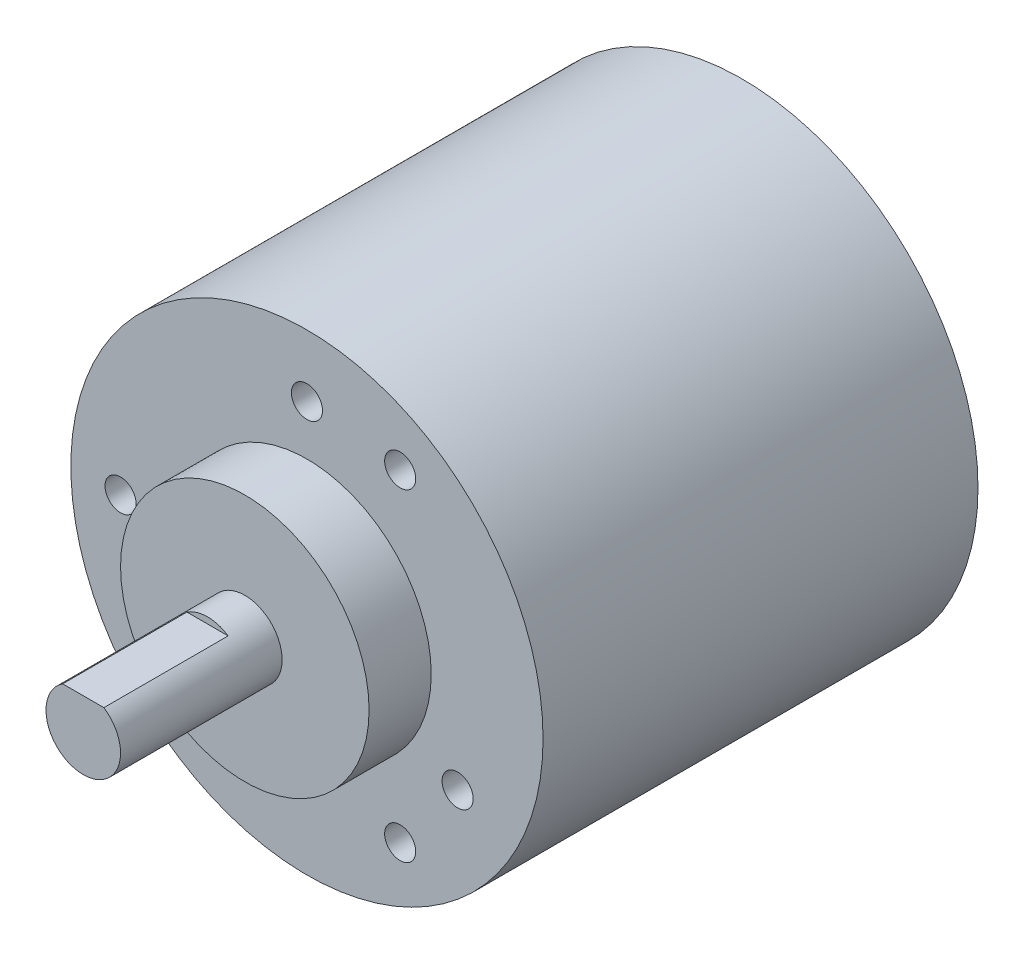
SolidWorks part; units mm, degrees
ref_plane "Front Plane" through (0, 0, 0) normal (0, 0, 1) x (1, 0, 0)
ref_plane "Top Plane" through (0, 0, 0) normal (0, 1, 0) x (1, 0, 0)
ref_plane "Right Plane" through (0, 0, 0) normal (1, 0, 0) x (0, 0, -1)
sketch "Sketch1" plane through (0, 0, 0) normal (0, 0, 1) x (1, 0, 0)
  circle A0 centre (0, 0) radius 19
  dimension "D1" = 38
extrude "Boss-Extrude1" add sketch "Sketch1" along normal blind 35 contours A0
sketch "Sketch2" plane through (0, 0, 35) normal (0, 0, 1) x (1, 0, 0)
  circle A0 centre (0, 0) radius 10
  dimension "D1" = 20
extrude "Boss-Extrude2" add sketch "Sketch2" along normal blind 5
sketch "Sketch3" plane through (0, 0, 40) normal (0, 0, 1) x (1, 0, 0)
  circle A0 centre (0, 0) radius 3
  dimension "D1" = 6
extrude "Boss-Extrude3" add sketch "Sketch3" along normal blind 13
sketch "Sketch4" plane through (0, 0, 53) normal (0, 0, 1) x (1, 0, 0)
  line L0 (-1.6583, 2.5) -> (1.6583, 2.5)
  circle A0 centre (0, 0) radius 3 construction
  arc A1 (1.6583, 2.5) -> (-1.6583, 2.5) centre (0, 0) ccw
  dimension "D1" = 0.5
extrude "Cut-Extrude1" cut sketch "Sketch4" against normal blind 10
hole_wizard "Tap Drill for M3x0.5 Tap1" positions "Sketch5" profile "Sketch6" hole size "M3x0.5" standard "ANSI Metric"
sketch "Sketch5" plane through (0, 0, 35) normal (0, 0, 1) x (1, 0, 0)
  line L0 (0, 14) -> (0, 0) construction
  line L1 (0, 0) -> (7.5, 12.9904) construction
  circle A1 centre (0, 0) radius 15 construction
  circle A2 centre (0, 0) radius 14 construction
  point P8 (0, 14)
  point P10 (7.5, 12.9904)
  point P19 (12.1244, -7)
  point P20 (7.5, -12.9904)
  point P21 (-12.1244, -7)
  point P22 (-15, 0)
  dimension "D1" = 30
  dimension "D2" = 28
  dimension "D3" = 30
  dimension "D4" = 3
sketch "Sketch6" plane through (-15, 0, 35) normal (1, 0, 0) x (0, -1, 0)
  line L0 (0, 0) -> (0, 5.7511)
  line L1 (0, 5.7511) -> (1.25, 5)
  line L2 (1.25, 5) -> (1.25, 0)
  line L5 (1.25, 0) -> (0, 0)
  line L10 (0, 5.7511) -> (-1.25, 5) construction
  line L11 (0, -6.35) -> (0, 107.95) construction
  dimension "Hole Dia." = 2.5
  dimension "Hole Depth" = 5
  dimension "Drill Angle" = 118
